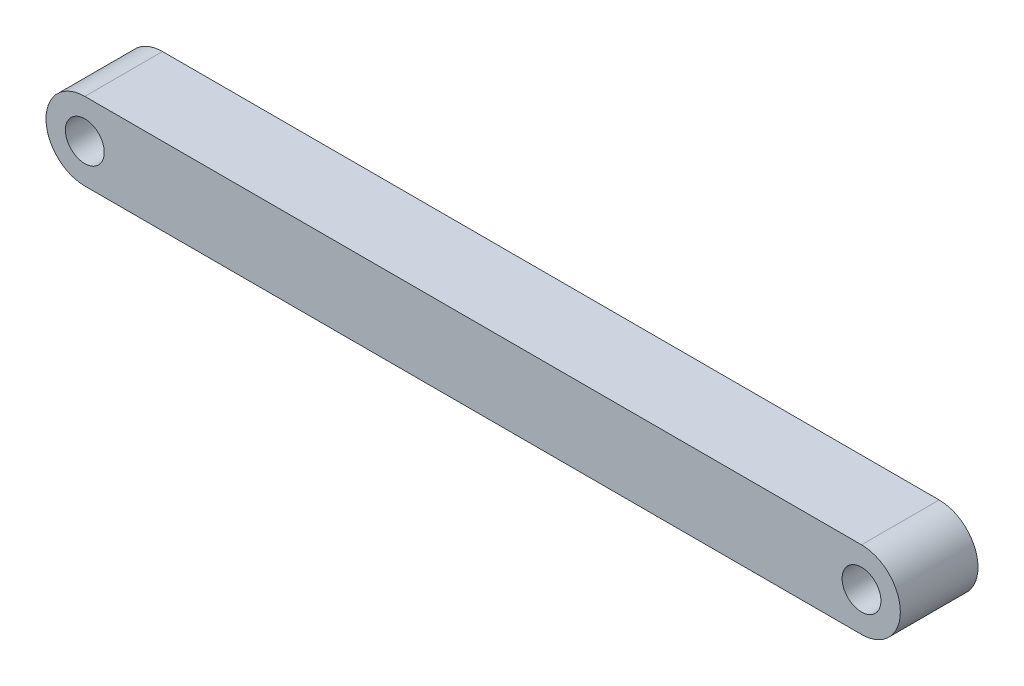
SolidWorks part; units mm, degrees
ref_plane "Front Plane" through (0, 0, 0) normal (0, 0, 1) x (1, 0, 0)
ref_plane "Top Plane" through (0, 0, 0) normal (0, 1, 0) x (1, 0, 0)
ref_plane "Right Plane" through (0, 0, 0) normal (1, 0, 0) x (0, 0, -1)
sketch "Sketch1" plane through (0, 0, 0) normal (0, 0, 1) x (1, 0, 0)
  line L0 (-25, 0) -> (25, 0) construction
  line L3 (-25, 2.5) -> (25, 2.5)
  line L4 (-25, -2.5) -> (25, -2.5)
  arc A2 (-25, 2.5) -> (-25, -2.5) centre (-25, 0) ccw
  arc A3 (25, -2.5) -> (25, 2.5) centre (25, 0) ccw
  circle A4 centre (-25, 0) radius 1.25
  circle A5 centre (25, 0) radius 1.25
  point P3 (0, 0)
  dimension "D1" = 2.5
  dimension "D2" = 2.5
  dimension "D3" = 5
  dimension "D4" = 50
extrude "Boss-Extrude1" add sketch "Sketch1" along normal blind 5
